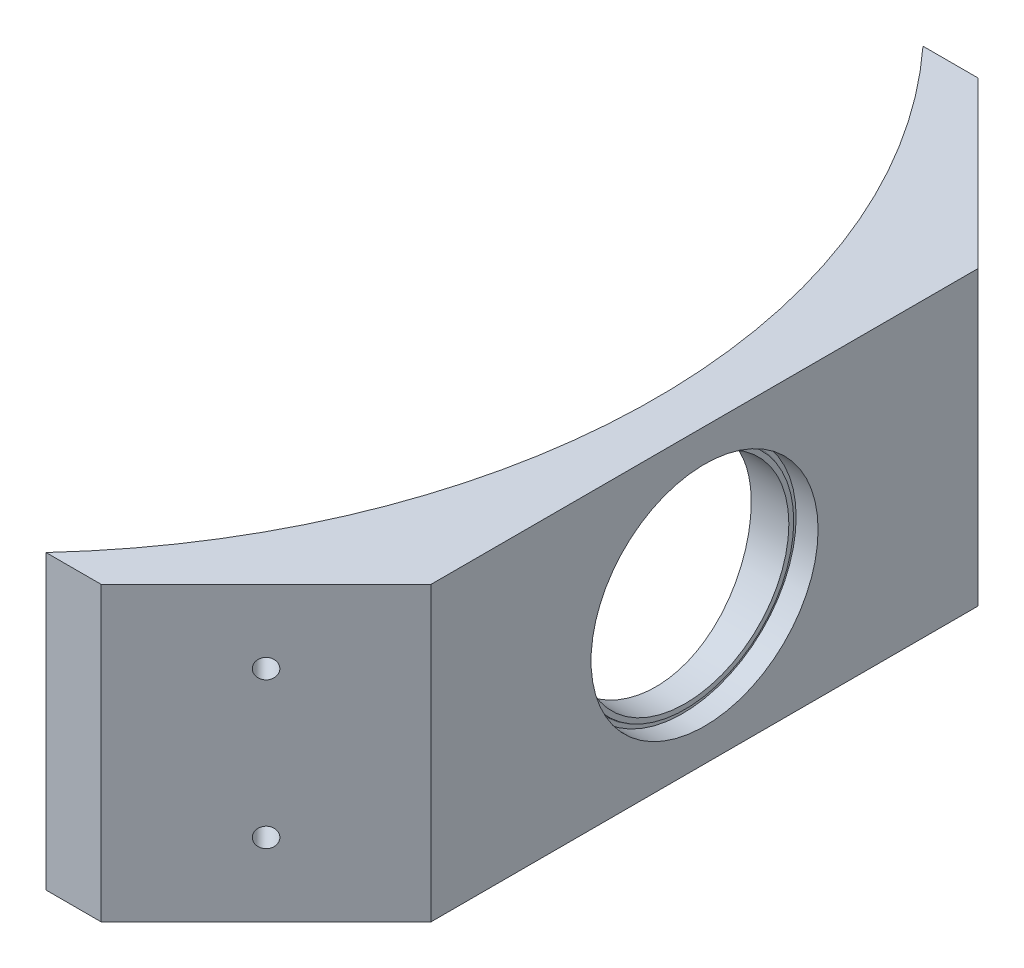
SolidWorks part; units mm, degrees
material "6061 Alloy"
ref_plane "Front Plane" through (0, 0, 0) normal (0, 0, 1) x (1, 0, 0)
ref_plane "Top Plane" through (0, 0, 0) normal (0, 1, 0) x (1, 0, 0)
ref_plane "Right Plane" through (0, 0, 0) normal (1, 0, 0) x (0, 0, -1)
sketch "Sketch1" plane through (0, 0, 0) normal (1, 0, 0) x (0, 0, -1)
  line L0 (44.8181, 64.7501) -> (49.8181, 64.7501)
  line L1 (-35.1819, 64.7501) -> (-40.1819, 64.7501)
  line L2 (-40.1819, 64.7501) -> (-40.1819, 34.7501)
  line L3 (-35.1819, 64.7501) -> (44.8181, 64.7501)
  line L4 (-40.1819, 34.7501) -> (-35.1819, 34.7501)
  line L5 (4.8181, 49.7501) -> (4.8181, 64.7501) construction
  line L6 (49.8181, 64.7501) -> (49.8181, 34.7501)
  line L7 (44.8181, 34.7501) -> (-35.1819, 34.7501)
  line L8 (49.8181, 34.7501) -> (44.8181, 34.7501)
  circle A0 centre (4.8181, 49.7501) radius 10.65
  point P2 (4.8181, 34.7501)
  dimension "D1" = 5
  dimension "D2" = 5
extrude "Boss-Extrude1" add sketch "Sketch1" along normal blind 4
sketch "Sketch4" plane through (4, 0, 0) normal (1, 0, 0) x (0, 0, -1)
  circle A0 centre (4.8181, 49.7501) radius 10.65
  circle A3 centre (4.8181, 49.7501) radius 11.65
extrude "Cut-Extrude2" cut sketch "Sketch4" against normal blind 2
sketch "Sketch5" plane through (2, 0, 0) normal (1, 0, 0) x (0, 0, -1)
  circle A0 centre (4.8181, 49.7501) radius 11.65
  circle A1 centre (4.8181, 49.7501) radius 11.15
  dimension "D1" = 0.5
extrude "Cut-Extrude3" cut sketch "Sketch5" against normal blind 0.25
fillet "Fillet1" radius 0.1 1 edges at (1.75, 49.7501, -15.9681)
sketch "Sketch11" plane through (0, 64.7501, 0) normal (0, 1, 0) x (1, 0, 0)
  line L0 (0, 4.8181) -> (-1, 4.8181) construction
  line L2 (-1, 4.8181) -> (-67.37, 4.8181) construction
  line L3 (0, 49.8181) -> (0, -40.1819)
  line L4 (0, 49.8181) -> (0, -40.1819) construction
  line L5 (0, 49.8181) -> (-18.585, 49.8181)
  line L6 (0, -40.1819) -> (-18.585, -40.1819)
  arc A1 (-18.585, -40.1819) -> (-18.585, 49.8181) centre (-67.37, 4.8181) ccw
  dimension "D1" = 1
extrude "Boss-Extrude3" add sketch "Sketch11" against normal blind 30
sketch "Sketch12" plane through (0, 0, 0) normal (1, 0, 0) x (0, 0, -1)
  circle A0 centre (4.8181, 49.7501) radius 10.65
extrude "Cut-Extrude6" cut sketch "Sketch12" against normal blind 30
sketch "Sketch13" plane through (0, 64.7501, 0) normal (0, 1, 0) x (1, 0, 0)
  line L0 (-18.585, 49.8181) -> (-7.2925, 49.8181) construction
  line L2 (4, 49.8181) -> (4, -40.1819) construction
  line L3 (4, 4.8181) -> (-14.9281, 4.8181) construction
  line L4 (4, 49.8181) -> (-18.585, 49.8181) construction
  line L5 (-12.9387, 49.8181) -> (4, 32.8793)
  line L6 (4, 32.8793) -> (4, 49.8181)
  line L7 (4, 49.8181) -> (-12.9387, 49.8181)
  line L8 (-12.9387, -40.1819) -> (4, -23.2432)
  line L9 (4, -23.2432) -> (4, -40.1819)
  line L10 (4, -40.1819) -> (-12.9387, -40.1819)
extrude "Cut-Extrude7" cut sketch "Sketch13" against normal blind 30
sketch "Sketch14" plane through (-109.6206, 0, 136.8638) normal (-0.7071, 0, -0.7071) x (-0.7071, 0, 0.7071)
  line L0 (-148.7063, 64.7501) -> (-148.7063, 49.7501) construction
  line L1 (-160.6838, 64.7501) -> (-136.7288, 64.7501) construction
  line L3 (-136.7288, 49.7501) -> (-160.6838, 49.7501) construction
  line L4 (-136.7288, 34.7501) -> (-136.7288, 64.7501) construction
  line L5 (-160.6838, 34.7501) -> (-160.6838, 64.7501) construction
  circle A0 centre (-148.7063, 57.2501) radius 1
  circle A1 centre (-148.7063, 42.2501) radius 1
  dimension "D1" = 2
extrude "Cut-Extrude8" cut sketch "Sketch14" along normal blind 30
sketch "Sketch15" plane through (18.5398, 0, -18.3395) normal (-0.7071, 0, 0.7071) x (0.7071, 0, 0.7071)
  line L0 (-32.3983, 49.7501) -> (-32.3983, 64.7501) construction
  line L1 (-20.156, 49.7501) -> (-44.7869, 49.7501) construction
  line L2 (-20.5624, 64.7501) -> (-44.5174, 64.7501) construction
  circle A0 centre (-32.3983, 57.2501) radius 1
  circle A1 centre (-32.3983, 42.2501) radius 1
extrude "Cut-Extrude9" cut sketch "Sketch15" along normal blind 30
